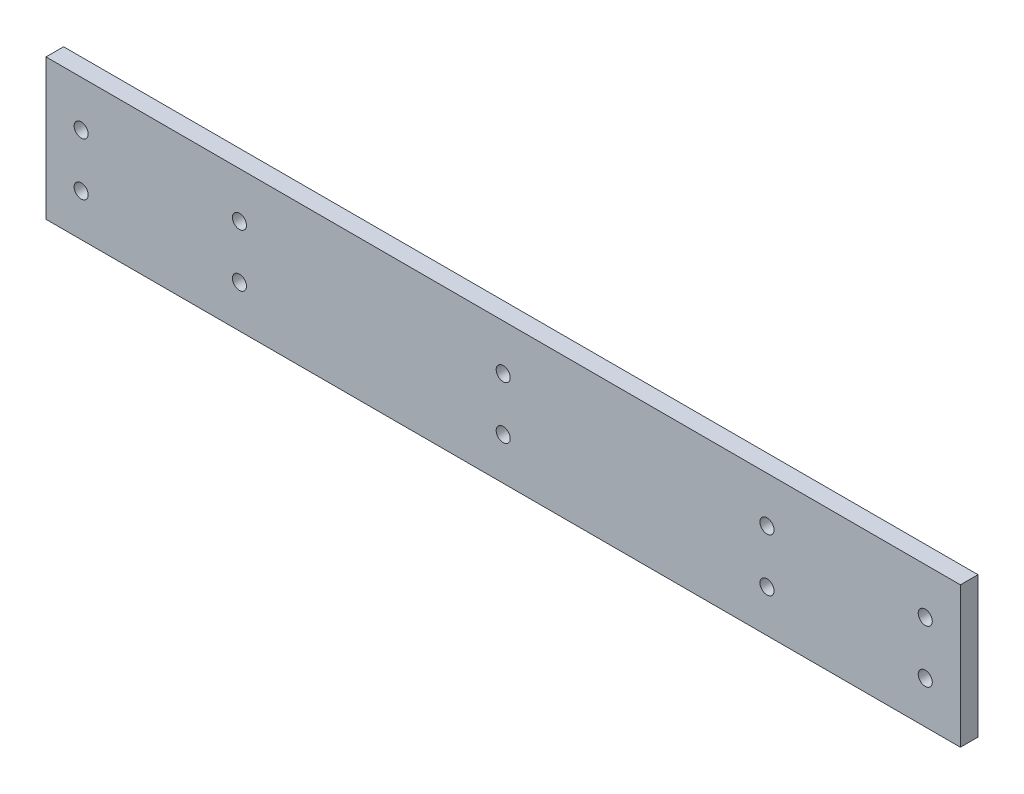
SolidWorks part; units mm, degrees
ref_plane "Plan de face" through (0, 0, 0) normal (0, 0, 1) x (1, 0, 0)
ref_plane "Plan de dessus" through (0, 0, 0) normal (0, 1, 0) x (1, 0, 0)
ref_plane "Plan de droite" through (0, 0, 0) normal (1, 0, 0) x (0, 0, -1)
sketch "Esquisse1" plane through (0, 0, 0) normal (0, 0, 1) x (1, 0, 0)
  line L1 (0, 0) -> (260, 0)
  line L2 (0, 0) -> (0, -40)
  line L3 (0, -40) -> (260, -40)
  line L4 (260, 0) -> (260, -40)
  dimension "D1" = 260
  dimension "D2" = 40
extrude "Boss.-Extru.1" add sketch "Esquisse1" along normal blind 5
sketch "Esquisse2" plane through (0, 0, 5) normal (0, 0, 1) x (1, 0, 0)
  line L0 (0, 0) -> (0, -40) construction
  line L1 (0, -40) -> (260, -40) construction
  line L2 (260, -40) -> (260, 0) construction
  circle A0 centre (10, -13) radius 2
  circle A1 centre (10, -28) radius 2
  circle A2 centre (250, -28) radius 2
  circle A3 centre (250, -13) radius 2
  circle A4 centre (205, -28) radius 2
  circle A5 centre (205, -13) radius 2
  circle A6 centre (55, -13) radius 2
  circle A7 centre (55, -28) radius 2
  circle A8 centre (130, -13) radius 2
  circle A9 centre (130, -28) radius 2
  dimension "D1" = 4
  dimension "D2" = 4
  dimension "D3" = 4
  dimension "D4" = 4
  dimension "D5" = 10
  dimension "D6" = 10
  dimension "D7" = 12
  dimension "D8" = 15
  dimension "D9" = 10
  dimension "D10" = 10
  dimension "D11" = 2
  dimension "D12" = 2
  dimension "D13" = 2
extrude "Enlèv. mat.-Extru.1" cut sketch "Esquisse2" against normal blind 5
